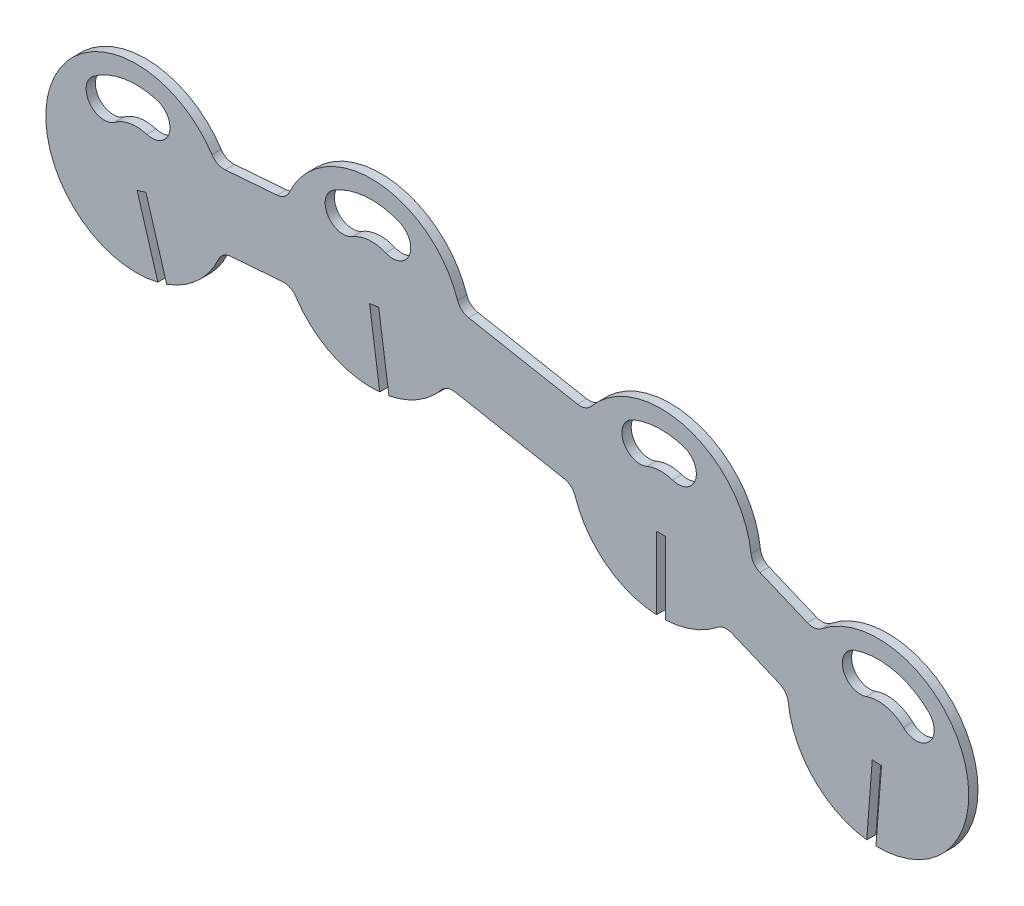
SolidWorks part; units mm, degrees
ref_plane "Front Plane" through (0, 0, 0) normal (0, 0, 1) x (1, 0, 0)
ref_plane "Top Plane" through (0, 0, 0) normal (0, 1, 0) x (1, 0, 0)
ref_plane "Right Plane" through (0, 0, 0) normal (1, 0, 0) x (0, 0, -1)
sketch "Sketch1" plane through (0, 0, 0) normal (0, 0, 1) x (1, 0, 0)
  line L0 (-51.2912, 76.2) -> (64262.6532, 76.2) construction
  line L5 (7.4715, 147.6375) -> (64321.4159, 147.6375) construction
  line L6 (118.3446, 158.75) -> (64432.2889, 158.75) construction
  line L7 (275.7842, 163.5125) -> (64589.7286, 163.5125) construction
  line L8 (55.5625, 439.4786) -> (55.5625, -63874.4658) construction
  line L9 (111.125, 452.7834) -> (111.125, -63861.161) construction
  line L10 (119.0625, 453.8921) -> (119.0625, -63860.0523) construction
  line L11 (99.4961, 73.025) -> (64413.4405, 73.025) construction
  line L12 (93.9525, 3.175) -> (64407.8969, 3.175) construction
  line L13 (33.9504, 0) -> (64347.8947, 0) construction
  line L14 (-39.0951, -3.175) -> (64274.8492, -3.175) construction
  line L15 (-110.0539, -73.025) -> (64203.8905, -73.025) construction
  line L16 (198.1731, 65.0875) -> (64512.1175, 65.0875) construction
  line L17 (201.4993, 77.7875) -> (64515.4437, 77.7875) construction
  line L18 (276.893, 155.575) -> (64590.8373, 155.575) construction
  line L19 (351.1779, 168.275) -> (64665.1223, 168.275) construction
  line L20 (107.95, 410.6516) -> (107.95, -63903.2928) construction
  line L21 (95.25, 453.8921) -> (95.25, -63860.0523) construction
  line L22 (87.3125, 480.5016) -> (87.3125, -63833.4428) construction
  line L23 (34.925, 470.523) -> (34.925, -63843.4213) construction
  line L24 (0, 558.1122) -> (0, -63755.8322) construction
  line L25 (127, 731.8887) -> (127, -63582.0557) construction
  line L26 (133.35, 785.5707) -> (133.35, -63528.3737) construction
  line L27 (146.05, 782.952) -> (146.05, -63530.9923) construction
  line L28 (147.6375, 792.1173) -> (147.6375, -63521.8271) construction
  line L29 (152.4, 819.6129) -> (152.4, -63494.3315) construction
  line L30 (161.925, 852.3458) -> (161.925, -63461.5986) construction
  line L31 (206.375, 822.2315) -> (206.375, -63491.7129) construction
  line L32 (-303.6442, 138.1125) -> (49696.3558, 138.1125) construction
  line L33 (-178.9515, 120.65) -> (49821.0485, 120.65) construction
  point P60 (111.125, -3.175)
  point P61 (119.0625, 0)
  point P62 (133.35, 3.175)
  point P63 (147.6375, 3.175)
  point P64 (107.95, 77.7875)
  point P65 (133.35, 73.025)
  point P66 (152.4, 65.0875)
  point P67 (87.3125, 76.2)
  point P68 (34.925, 147.6375)
  point P69 (55.5625, 163.5125)
  point P70 (111.125, 155.575)
  point P71 (95.25, 163.5125)
  point P72 (127, 138.1125)
  point P73 (146.05, 168.275)
  point P74 (161.925, 158.75)
  point P77 (206.375, 120.65)
  dimension "D1" = 69.85
  dimension "D2" = 73.025
  dimension "D3" = 76.2
  dimension "D4" = 138.1125
  dimension "D5" = 146.05
  dimension "D6" = 150.8125
  dimension "D7" = 149.225
  dimension "D8" = 211.1375
  dimension "D9" = 220.6625
  dimension "D10" = 228.6
  dimension "D11" = 231.775
  dimension "D12" = 236.5375
  dimension "D13" = 241.3
  dimension "D14" = 34.925
  dimension "D15" = 55.5625
  dimension "D16" = 87.3125
  dimension "D17" = 95.25
  dimension "D18" = 107.95
  dimension "D19" = 111.125
  dimension "D20" = 119.0625
  dimension "D21" = 127
  dimension "D22" = 133.35
  dimension "D23" = 146.05
  dimension "D24" = 147.6375
  dimension "D25" = 152.4
  dimension "D26" = 161.925
  dimension "D27" = 206.375
  dimension "D28" = 193.675
sketch "Sketch2" plane through (0, 0, 0) normal (0, 0, 1) x (1, 0, 0)
  line L0 (111.125, -3.175) -> (87.3125, 76.2)
  line L1 (119.0625, 0) -> (107.95, 77.7875)
  line L2 (133.35, 3.175) -> (133.35, 73.025)
  line L3 (147.6375, 3.175) -> (152.4, 65.0875)
  line L4 (152.4, 65.0875) -> (206.375, 120.65)
  line L5 (152.4, 65.0875) -> (127, 138.1125)
  line L6 (133.35, 73.025) -> (161.925, 158.75)
  line L7 (-199881.6554, 158.75) -> (264432.2889, 158.75) construction
  line L8 (133.35, 73.025) -> (95.25, 163.5125)
  line L9 (107.95, 77.7875) -> (146.05, 168.275)
  line L10 (107.95, 77.7875) -> (55.5625, 163.5125)
  line L11 (87.3125, 76.2) -> (111.125, 155.575)
  line L12 (87.3125, 76.2) -> (34.925, 147.6375)
sketch "Sketch4" plane through (0, 0, 0) normal (0, 0, 1) x (1, 0, 0)
  line L0 (87.3125, 76.2) -> (107.95, 77.7875) construction
  line L1 (107.95, 77.7875) -> (133.35, 73.025) construction
  line L2 (133.35, 73.025) -> (152.4, 65.0875) construction
  line L3 (94.8094, 73.5923) -> (100.9401, 74.0639)
  line L4 (114.5151, 73.3262) -> (125.6146, 71.2451)
  line L5 (138.8441, 67.2962) -> (146.05, 64.2937)
  line L6 (111.125, -3.175) -> (87.3125, 76.2) construction
  line L7 (107.5477, 77.73) -> (108.6702, 69.8723) construction
  line L8 (141.2864, 73.1578) -> (146.9059, 70.8163)
  line L9 (87.069, 79.3656) -> (108.1238, 80.9852) construction
  line L10 (87.556, 73.0344) -> (107.7762, 74.5898) construction
  line L11 (134.2631, 76.0841) -> (153.6212, 68.0183) construction
  line L12 (132.4369, 69.9659) -> (151.1788, 62.1567) construction
  line L13 (146.05, 200782.952) -> (146.05, -263530.9923) construction
  line L14 (108.1238, 80.9852) -> (134.2631, 76.0841) construction
  line L15 (107.7762, 74.5898) -> (132.4369, 69.9659) construction
  line L16 (108.3523, 77.845) -> (109.4748, 69.9872) construction
  line L17 (107.7722, 76.1585) -> (108.5768, 76.2734)
  line L18 (94.3224, 79.9236) -> (100.4531, 80.3952)
  line L19 (115.6854, 79.5674) -> (126.7849, 77.4863)
  line L20 (132.9436, 73.025) -> (132.9436, 65.0875) construction
  line L21 (133.7564, 73.025) -> (133.7564, 65.0875) construction
  line L22 (132.9436, 71.4479) -> (133.7564, 71.4479)
  line L23 (151.8738, 63.5462) -> (151.3868, 57.2149)
  line L24 (152.6842, 63.4839) -> (152.1972, 57.1526)
  line L25 (151.8738, 63.5462) -> (152.6842, 63.4839)
  line L26 (152.4, 65.0875) -> (206.375, 120.65) construction
  line L27 (152.4, 65.0875) -> (127, 138.1125) construction
  line L28 (133.35, 73.025) -> (161.925, 158.75) construction
  line L29 (133.35, 73.025) -> (95.25, 163.5125) construction
  line L30 (87.3125, 76.2) -> (89.5933, 68.5973)
  line L31 (107.95, 77.7875) -> (109.0725, 69.9298)
  line L32 (119.0625, 0) -> (107.95, 77.7875) construction
  line L33 (133.35, 73.025) -> (133.35, 65.0875)
  line L34 (152.4, 65.0875) -> (151.7912, 57.1734)
  line L35 (147.6375, 3.175) -> (152.4, 65.0875) construction
  line L36 (87.3794, 74.5627) -> (89.2011, 68.4904)
  line L37 (107.7722, 76.1585) -> (108.6687, 69.8826)
  line L38 (132.9436, 71.4479) -> (132.9436, 65.0979)
  line L39 (107.95, 77.7875) -> (146.05, 168.275) construction
  line L40 (88.1579, 74.7962) -> (89.9796, 68.724)
  line L41 (108.5768, 76.2734) -> (109.4734, 69.9976)
  line L42 (133.7564, 71.4479) -> (133.7564, 65.0979)
  line L43 (107.95, 77.7875) -> (55.5625, 163.5125) construction
  line L44 (87.7018, 76.3168) -> (89.9826, 68.714) construction
  line L45 (86.9232, 76.0832) -> (89.2041, 68.4805) construction
  line L46 (87.3794, 74.5627) -> (88.1579, 74.7962)
  line L47 (87.3125, 76.2) -> (111.125, 155.575) construction
  line L48 (87.3125, 76.2) -> (34.925, 147.6375) construction
  circle A0 centre (87.3125, 76.2) radius 7.9375
  circle A1 centre (107.95, 77.7875) radius 7.9375
  circle A2 centre (133.35, 73.025) radius 7.9375
  circle A3 centre (152.4, 65.0875) radius 7.9375
  circle A4 centre (95.0113, 81.2503) radius 1.27
  circle A5 centre (99.5693, 81.601) radius 1.27
  circle A6 centre (116.6946, 80.6704) radius 1.27
  circle A7 centre (126.2438, 78.8799) radius 1.27
  circle A8 centre (142.5028, 74.0267) radius 1.27
  circle A9 centre (146.6664, 72.2919) radius 1.27
  circle A10 centre (143.2472, 64.0858) radius 1.27
  circle A11 centre (139.0836, 65.8206) radius 1.27
  circle A12 centre (124.6054, 70.1421) radius 1.27
  circle A13 centre (115.0562, 71.9326) radius 1.27
  circle A14 centre (100.2512, 72.7372) radius 1.27
  circle A15 centre (95.6932, 72.3865) radius 1.27
  circle A16 centre (152.4, 65.0875) radius 4.7625 construction
  circle A17 centre (133.35, 73.025) radius 4.7625 construction
  circle A18 centre (107.95, 77.7875) radius 4.7625 construction
  circle A19 centre (87.3125, 76.2) radius 4.7625 construction
  circle A20 centre (155.7184, 68.5035) radius 1.5875
  circle A21 centre (150.8354, 69.5857) radius 1.5875
  circle A22 centre (134.856, 77.5431) radius 1.5875
  circle A23 centre (131.5019, 77.4143) radius 1.5875
  circle A24 centre (109.7981, 82.1768) radius 1.5875
  circle A25 centre (105.4666, 81.8513) radius 1.5875
  circle A26 centre (88.681, 80.7616) radius 1.5875
  circle A27 centre (84.4961, 80.0405) radius 1.5875
  arc A28 (154.6123, 67.3649) -> (151.3569, 68.0863) centre (152.4, 65.0875) ccw
  arc A29 (156.8246, 69.6422) -> (150.3139, 71.0851) centre (152.4, 65.0875) ccw
  arc A30 (134.354, 76.0371) -> (132.1179, 75.9512) centre (133.35, 73.025) ccw
  arc A31 (130.8858, 78.8774) -> (135.358, 79.0491) centre (133.35, 73.025) cw
  arc A32 (109.1821, 80.7137) -> (106.2944, 80.4967) centre (107.95, 77.7875) ccw
  arc A33 (110.4142, 83.6399) -> (104.6388, 83.2058) centre (107.95, 77.7875) ccw
  arc A34 (88.2248, 79.2411) -> (85.4349, 78.7603) centre (87.3125, 76.2) ccw
  arc A35 (89.1372, 82.2822) -> (83.5573, 81.3207) centre (87.3125, 76.2) ccw
  dimension "D1" = 15.875
  dimension "D6" = 2.54
  dimension "D15" = 9.525
  dimension "D16" = 3.175
  dimension "D2" = 3.175
  dimension "D4" = 3.175
  dimension "D5" = 3.175
  dimension "D7" = 0.4064
  dimension "D9" = 6.35
  dimension "D10" = 6.35
  dimension "D11" = 6.35
  dimension "D12" = 0.4064
  dimension "D14" = 6.35
  dimension "D13" = 0.4064
  dimension "D3" = 3.175
  dimension "D8" = 0.4064
extrude "Boss-Extrude1" add sketch "Sketch4" along normal blind 0.8128
